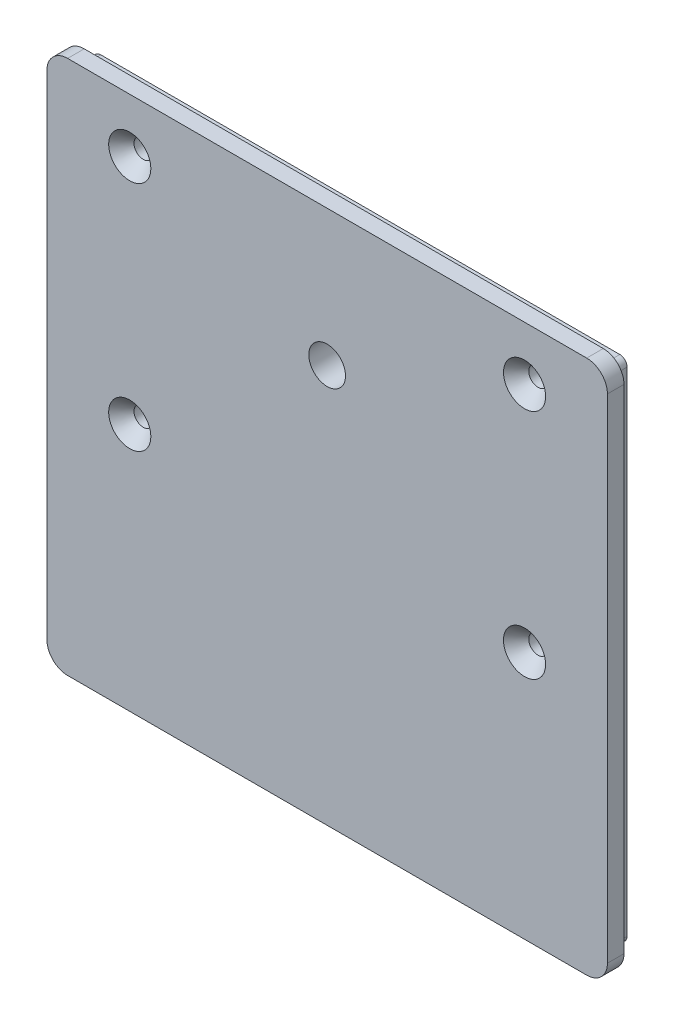
SolidWorks part; units mm, degrees
ref_plane "Front Plane" through (0, 0, 0) normal (0, 0, 1) x (1, 0, 0)
ref_plane "Top Plane" through (0, 0, 0) normal (0, 1, 0) x (1, 0, 0)
ref_plane "Right Plane" through (0, 0, 0) normal (1, 0, 0) x (0, 0, -1)
sketch "Sketch2" plane through (0, 0, 0) normal (0, 1, 0) x (1, 0, 0)
  line L0 (-70.95, 0) -> (70.95, 0) construction
  line L1 (-52.7926, 109.8893) -> (62.5, 109.8893)
  line L2 (-52.7926, 109.8893) -> (-52.7926, -24.1107)
  line L3 (-52.7926, -24.1107) -> (62.5, -24.1107)
  line L4 (62.5, 109.8893) -> (62.5, -24.1107)
  line L5 (0, -4.4) -> (0, 4.4) construction
  dimension "D1" = 109.8893
  dimension "D2" = 24.1107
  dimension "D3" = 62.5
  dimension "D4" = 52.7926
extrude "Boss-Extrude2" add sketch "Sketch2" along normal blind 8 contours L2 L1 L4 L3
fillet "Fillet2" radius 6 2 edges at (62.5, 4, -109.8893) (-52.7926, 4, -109.8893)
sketch "Sketch19" plane through (-52.7926, 0, 0) normal (-1, 0, 0) x (0, 0, 1)
  line L0 (24.1107, 8) -> (24.1107, 0) construction
  line L1 (24.1107, -36) -> (32.1107, -36)
  line L2 (24.1107, -36) -> (24.1107, 63)
  line L3 (24.1107, 63) -> (32.1107, 63)
  line L4 (32.1107, -36) -> (32.1107, 63)
  line L5 (-103.8893, 8) -> (24.1107, 8) construction
  line L6 (-103.8893, 0) -> (24.1107, 0) construction
  dimension "D1" = 8
  dimension "D2" = 55
  dimension "D3" = 36
extrude "Boss-Extrude3" add sketch "Sketch19" against normal up to surface (115.2926 mm away) up to face at (62.5, 4, -39.8893)
sketch "Sketch21" plane through (0, 0, 32.1107) normal (0, 0, 1) x (1, 0, 0)
  line L0 (72.5, 73) -> (-62.7926, 73)
  line L1 (-62.7926, 73) -> (-62.7926, -56)
  line L2 (-62.7926, -56) -> (72.5, -56)
  line L3 (72.5, -56) -> (72.5, 73)
  line L4 (-52.7926, -36) -> (62.5, -36)
  line L5 (62.5, -36) -> (62.5, 63)
  line L6 (62.5, 63) -> (-52.7926, 63)
  line L7 (-52.7926, 63) -> (-52.7926, -36)
  line L8 (-52.7926, -36) -> (62.5, -36)
  line L9 (62.5, -36) -> (62.5, 63)
  line L10 (62.5, 63) -> (-52.7926, 63)
  line L11 (-52.7926, 63) -> (-52.7926, -36)
  line L12 (62.5, -36) -> (-52.7926, -36) construction
  dimension "D3" = 10
  dimension "D2" = 10
  dimension "D4" = 10
  dimension "D5" = 20
  dimension "D1" = 0
extrude "Boss-Extrude4" add sketch "Sketch21" against normal up to surface (8 mm away) up to face at (4.8537, 35.5, 24.1107)
fillet "Fillet3" radius 5 4 edges at (-62.7926, 73, 28.1107) (72.5, 73, 28.1107) (72.5, -56, 28.1107) (-62.7926, -56, 28.1107)
sketch "Sketch22" plane through (0, 0, 24.1107) normal (0, 0, -1) x (-1, 0, 0)
  line L0 (57.7926, 69.75) -> (-67.5, 69.75)
  line L1 (-69.25, 68) -> (-69.25, -51)
  line L2 (-67.5, -52.75) -> (57.7926, -52.75)
  line L3 (59.5426, -51) -> (59.5426, 68)
  line L4 (62.7926, -51) -> (62.7926, 68)
  line L5 (57.7926, 73) -> (-67.5, 73)
  line L6 (-72.5, 68) -> (-72.5, -51)
  line L7 (-67.5, -56) -> (57.7926, -56)
  line L8 (62.7926, -51) -> (62.7926, 68)
  line L9 (57.7926, 73) -> (-67.5, 73)
  line L10 (-72.5, 68) -> (-72.5, -51)
  line L11 (-67.5, -56) -> (57.7926, -56)
  arc A0 (-67.5, 69.75) -> (-69.25, 68) centre (-67.5, 68) ccw
  arc A1 (-69.25, -51) -> (-67.5, -52.75) centre (-67.5, -51) ccw
  arc A2 (57.7926, -52.75) -> (59.5426, -51) centre (57.7926, -51) ccw
  arc A3 (59.5426, 68) -> (57.7926, 69.75) centre (57.7926, 68) ccw
  arc A4 (62.7926, 68) -> (57.7926, 73) centre (57.7926, 68) ccw
  arc A5 (-67.5, 73) -> (-72.5, 68) centre (-67.5, 68) ccw
  arc A6 (-72.5, -51) -> (-67.5, -56) centre (-67.5, -51) ccw
  arc A7 (57.7926, -56) -> (62.7926, -51) centre (57.7926, -51) ccw
  arc A8 (62.7926, 68) -> (57.7926, 73) centre (57.7926, 68) ccw
  arc A9 (-67.5, 73) -> (-72.5, 68) centre (-67.5, 68) ccw
  arc A10 (-72.5, -51) -> (-67.5, -56) centre (-67.5, -51) ccw
  arc A11 (57.7926, -56) -> (62.7926, -51) centre (57.7926, -51) ccw
  dimension "D1" = 0
  dimension "D2" = 3.25
extrude "Cut-Extrude1" cut sketch "Sketch22" against normal blind 4
sketch "Sketch24" plane through (0, 0, 24.1107) normal (0, 0, -1) x (-1, 0, 0)
  line L0 (-62.5, 8) -> (-62.5, 69.75) construction
  line L1 (57.7926, 69.75) -> (-67.5, 69.75) construction
  line L2 (52.7926, 8) -> (52.7926, 69.75) construction
  line L3 (-62.5, 55) -> (52.7926, 55) construction
  line L4 (52.7926, 8) -> (-62.5, 8) construction
  line L6 (-62.5, 55) -> (52.7926, 55)
  line L7 (-62.5, 55) -> (-62.5, 65)
  line L8 (-62.5, 65) -> (52.7926, 65)
  line L9 (52.7926, 55) -> (52.7926, 65)
  dimension "D1" = 47
  dimension "D2" = 10
extrude "Boss-Extrude5" add sketch "Sketch24" along normal blind 104
fillet "Fillet4" radius 6 2 edges at (62.5, 60, -79.8893) (-52.7926, 60, -79.8893)
sketch "Sketch49" plane through (0, 0, 32.1107) normal (0, 0, 1) x (1, 0, 0)
  line L0 (4.8537, 40.1596) -> (4.8537, -56) construction
  line L2 (-57.7926, -56) -> (67.5, -56) construction
  line L3 (-62.7926, 40.1596) -> (4.8537, 40.1596) construction
  line L4 (-62.7926, 68) -> (-62.7926, -51) construction
  circle A0 centre (4.8537, 40.1596) radius 4.43
  dimension "D1" = 8.86
extrude "Cut-Extrude3" cut sketch "Sketch49" against normal up to surface (8 mm away) up to face at (4.8537, 4, 24.1107)
hole_wizard "M2.5 Clearance Hole1" positions "Sketch58" profile "Sketch59" hole size "M2.5" standard "ANSI Metric" end condition through all
sketch "Sketch58" plane through (0, 8, 0) normal (0, 1, 0) x (1, 0, 0)
  line L0 (-28.27, 101.64) -> (-7.29, 101.64) construction
  line L1 (-7.29, 101.64) -> (-7.29, 88.14) construction
  line L2 (-7.29, 88.14) -> (-28.27, 88.14) construction
  line L3 (-28.27, 88.14) -> (-28.27, 101.64) construction
  line L6 (-70.95, 0) -> (70.95, 0) construction
  line L7 (0, -4.4) -> (0, 4.4) construction
  point P0 (-28.27, 101.64)
  point P2 (-7.29, 101.64)
  point P4 (-7.29, 88.14)
  point P6 (-28.27, 88.14)
  dimension "D1" = 88.14
  dimension "D2" = 28.27
  dimension "D3" = 7.29
  dimension "D4" = 101.64
sketch "Sketch59" plane through (-28.27, 8, -101.64) normal (1, 0, 0) x (0, 0, 1)
  line L0 (0, 0) -> (0, 64)
  line L1 (0, 64) -> (1.45, 64)
  line L2 (1.45, 64) -> (1.45, 0)
  line L5 (1.45, 0) -> (0, 0)
  line L11 (0, -6.35) -> (0, 107.95) construction
  dimension "Thru Hole Dia." = 2.9
  dimension "Thru Hole Depth" = 64
sketch "Sketch60" plane through (0, 8, 0) normal (0, 1, 0) x (1, 0, 0)
  line L0 (-30.27, 101.64) -> (-26.27, 101.64) construction
  line L1 (-30.27, 103.09) -> (-26.27, 103.09)
  line L2 (-30.27, 100.19) -> (-26.27, 100.19)
  line L3 (-9.29, 101.64) -> (-5.29, 101.64) construction
  line L4 (-9.29, 103.09) -> (-5.29, 103.09)
  line L5 (-9.29, 100.19) -> (-5.29, 100.19)
  line L6 (-30.27, 88.14) -> (-26.27, 88.14) construction
  line L7 (-30.27, 89.59) -> (-26.27, 89.59)
  line L8 (-30.27, 86.69) -> (-26.27, 86.69)
  line L9 (-9.29, 88.14) -> (-5.29, 88.14) construction
  line L10 (-9.29, 89.59) -> (-5.29, 89.59)
  line L11 (-9.29, 86.69) -> (-5.29, 86.69)
  arc A0 (-30.27, 103.09) -> (-30.27, 100.19) centre (-30.27, 101.64) ccw
  arc A1 (-26.27, 100.19) -> (-26.27, 103.09) centre (-26.27, 101.64) ccw
  arc A2 (-9.29, 103.09) -> (-9.29, 100.19) centre (-9.29, 101.64) ccw
  arc A3 (-5.29, 100.19) -> (-5.29, 103.09) centre (-5.29, 101.64) ccw
  arc A4 (-30.27, 89.59) -> (-30.27, 86.69) centre (-30.27, 88.14) ccw
  arc A5 (-26.27, 86.69) -> (-26.27, 89.59) centre (-26.27, 88.14) ccw
  arc A6 (-9.29, 89.59) -> (-9.29, 86.69) centre (-9.29, 88.14) ccw
  arc A7 (-5.29, 86.69) -> (-5.29, 89.59) centre (-5.29, 88.14) ccw
  circle A8 centre (-28.27, 101.64) radius 1.45 construction
  point P2 (-28.27, 101.64)
  point P9 (-7.29, 101.64)
  point P17 (-28.27, 88.14)
  point P25 (-7.29, 88.14)
  dimension "D1" = 4
extrude "Cut-Extrude4" cut sketch "Sketch60" against normal up to next
chamfer "Chamfer1" distance 0.9 angle 45 16 edges at (-7.29, 8, -100.19) (-3.84, 8, -101.64) (-10.74, 8, -101.64) (-7.29, 8, -103.09) (-7.29, 8, -86.69) (-3.84, 8, -88.14) (-10.74, 8, -88.14) (-7.29, 8, -89.59) (-28.27, 8, -86.69) (-24.82, 8, -88.14) (-31.72, 8, -88.14) (-28.27, 8, -89.59) (-28.27, 8, -103.09) (-31.72, 8, -101.64) (-24.82, 8, -101.64) (-28.27, 8, -100.19)
sketch "Sketch61" plane through (0, 65, 0) normal (0, 1, 0) x (1, 0, 0)
  line L0 (62.5, 73.8893) -> (62.5, -24.1107) construction
  line L1 (-52.7926, -24.1107) -> (62.5, -24.1107)
  line L2 (-52.7926, -24.1107) -> (-52.7926, 109.8893)
  line L3 (-52.7926, 109.8893) -> (62.5, 109.8893)
  line L4 (62.5, -24.1107) -> (62.5, 109.8893)
  line L5 (-46.7926, 109.8893) -> (56.5, 109.8893) construction
hole_wizard "CSK for #8 Flat Head Machine Screw1" positions "Sketch63" profile "Sketch64" countersink size "#8" standard "ANSI Inch"
sketch "Sketch63" plane through (0, 0, 32.1107) normal (0, 0, 1) x (1, 0, 0)
  line L6 (4.4, 0) -> (-4.4, 0) construction
  line L7 (0, -4.4) -> (0, 4.4) construction
  point P0 (-42.7926, 60)
  point P2 (52.5, 60)
  point P5 (-42.7926, 4)
  point P7 (52.5, 4)
  dimension "D1" = 4
  dimension "D2" = 60
  dimension "D3" = 42.7926
  dimension "D4" = 42.7926
  dimension "D5" = 52.5
  dimension "D6" = 52.5
sketch "Sketch64" plane through (-42.7926, 60, 32.1107) normal (1, 0, 0) x (0, -1, 0)
  line L0 (0, 0) -> (0, 9.3507)
  line L1 (0, 9.3507) -> (2.2479, 8)
  line L2 (2.2479, 8) -> (2.2479, 3.2645)
  line L3 (2.2479, 3.2645) -> (5.0857, 0)
  line L5 (5.0857, 0) -> (0, 0)
  line L6 (-2.2479, 3.2645) -> (-5.0857, 0) construction
  line L10 (0, 9.3507) -> (-2.2479, 8) construction
  line L11 (0, -6.35) -> (0, 107.95) construction
  dimension "Hole Dia." = 4.4958
  dimension "Hole Depth" = 8
  dimension "Near C'Sink Dia." = 10.1714
  dimension "Near C'Sink Angle" = 82
  dimension "Drill Angle" = 118
extrude "Cut-Extrude6" cut sketch "Sketch61" against normal up to surface (65 mm away) up to face at (-28.27, 0, -101.64)
